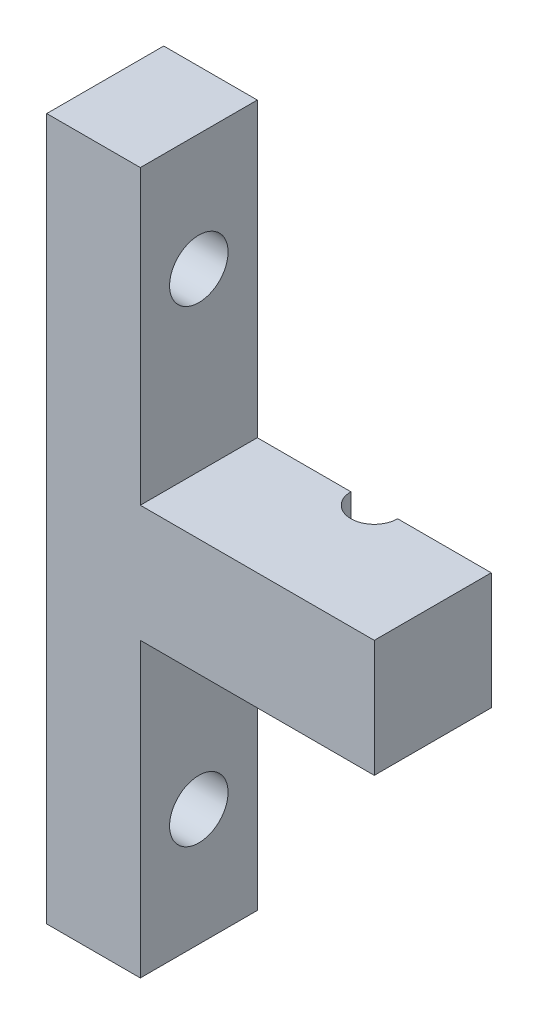
SolidWorks part; units mm, degrees
ref_plane "Front Plane" through (0, 0, 0) normal (0, 0, 1) x (1, 0, 0)
ref_plane "Top Plane" through (0, 0, 0) normal (0, 1, 0) x (1, 0, 0)
ref_plane "Right Plane" through (0, 0, 0) normal (1, 0, 0) x (0, 0, -1)
sketch "Sketch1" plane through (0, 0, 0) normal (0, 1, 0) x (1, 0, 0)
  line L1 (0, 0) -> (4, 0)
  line L2 (0, 0) -> (0, -5)
  line L3 (0, -5) -> (4, -5)
  line L4 (4, 0) -> (4, -5)
  dimension "D1" = 4
  dimension "D2" = 5
extrude "Boss-Extrude1" add sketch "Sketch1" along normal blind 30
sketch "Sketch2" plane through (4, 0, 0) normal (1, 0, 0) x (0, 0, -1)
  line L0 (-5, 30) -> (-5, 0) construction
  line L1 (-5, 17.5) -> (0, 17.5)
  line L2 (-5, 17.5) -> (-5, 12.5)
  line L3 (-5, 12.5) -> (0, 12.5)
  line L4 (0, 17.5) -> (0, 12.5)
  line L5 (0, 30) -> (0, 0) construction
  line L6 (-5, 0) -> (0, 0) construction
  dimension "D1" = 5
  dimension "D2" = 12.5
extrude "Boss-Extrude2" add sketch "Sketch2" along normal blind 10
sketch "Sketch3" plane through (4, 0, 0) normal (1, 0, 0) x (0, 0, -1)
  line L1 (-5, 30) -> (0, 30) construction
  line L4 (-5, 15) -> (0, 15) construction
  line L5 (-5, 17.5) -> (-5, 12.5) construction
  line L6 (0, 12.5) -> (0, 17.5) construction
  line L7 (0, 30) -> (0, 17.5) construction
  circle A0 centre (-2.5, 25) radius 1.25
  circle A1 centre (-2.5, 5) radius 1.25
  point P3 (0, 0)
  point P5 (0, 0)
  point P6 (0, 0)
  point P16 (0, 0)
  point P17 (-2.5, 23.8276)
  dimension "D1" = 2.5
  dimension "D2" = 5
  dimension "D3" = 2.5
extrude "Cut-Extrude1" cut sketch "Sketch3" against normal through all
sketch "Sketch4" plane through (0, 0, 0) normal (0, 1, 0) x (1, 0, 0)
  line L4 (14, 0) -> (4, 0) construction
  line L5 (8, 0) -> (10, 0)
  line L6 (4, -5) -> (4, 0) construction
  arc A1 (8, 0) -> (10, 0) centre (9, 0) ccw
  point P3 (0, 0)
  dimension "D2" = 5
  dimension "D1" = 1
extrude "Cut-Extrude2" cut sketch "Sketch4" along normal through all
